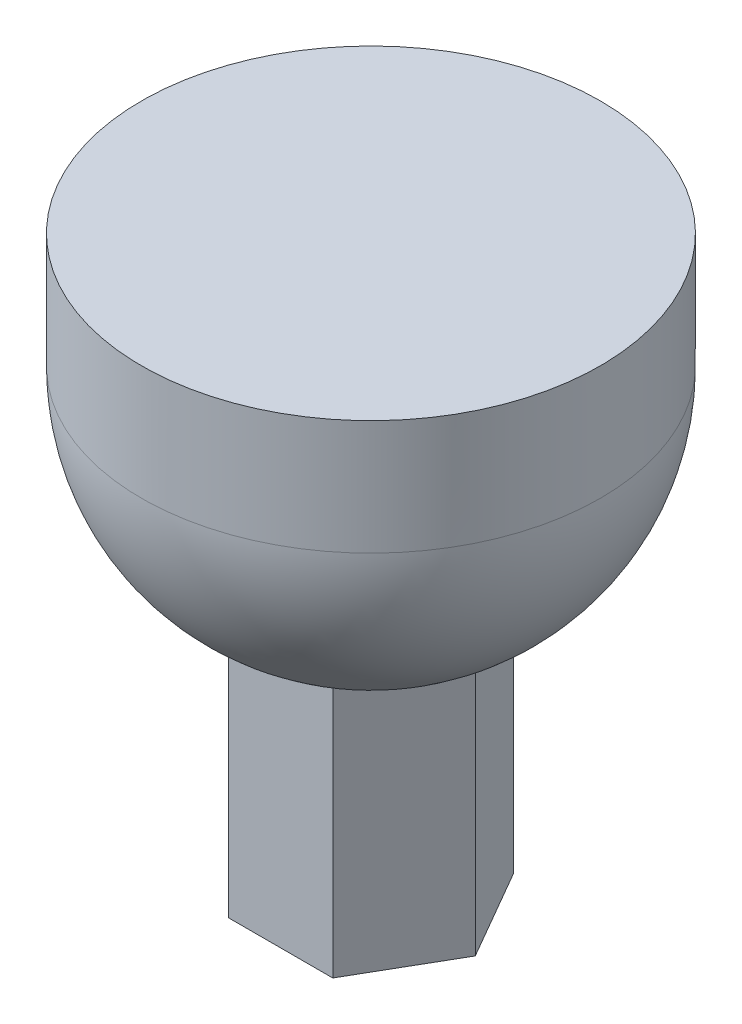
SolidWorks part; units mm, degrees
ref_plane "Front" through (0, 0, 0) normal (0, 0, 1) x (1, 0, 0)
ref_plane "Top" through (0, 0, 0) normal (0, 1, 0) x (1, 0, 0)
ref_plane "Right" through (0, 0, 0) normal (1, 0, 0) x (0, 0, -1)
sketch "Sketch2" plane through (0, 0, 0) normal (0, 0, 1) x (1, 0, 0)
  line L1 (0, 12.7) -> (0, -25.4)
  line L4 (0, 12.7) -> (25.4, 12.7)
  line L5 (25.4, 0) -> (25.4, 12.7)
  arc A0 (0, -25.4) -> (25.4, 0) centre (0, 0) ccw
  dimension "D1" = 50.8
  dimension "D2" = 12.7
ref_axis "Axis1" through (0, -50, 0) along (0, 1, 0)
revolve "Revolve3" add sketch "Sketch2" angle 360 about axis through (0, -50, 0) along (0, 1, 0)
sketch "Sketch3" plane through (0, 0, 0) normal (0, 1, 0) x (1, 0, 0)
  line L1 (-5.7735, -10) -> (5.7735, -10)
  line L2 (5.7735, -10) -> (11.547, 0)
  line L3 (11.547, 0) -> (5.7735, 10)
  line L4 (5.7735, 10) -> (-5.7735, 10)
  line L5 (-5.7735, 10) -> (-11.547, 0)
  line L6 (-11.547, 0) -> (-5.7735, -10)
  circle A0 centre (0, 0) radius 10 construction
  dimension "D1" = 20
extrude "Boss-Extrude1" add sketch "Sketch3" against normal blind 50.8
